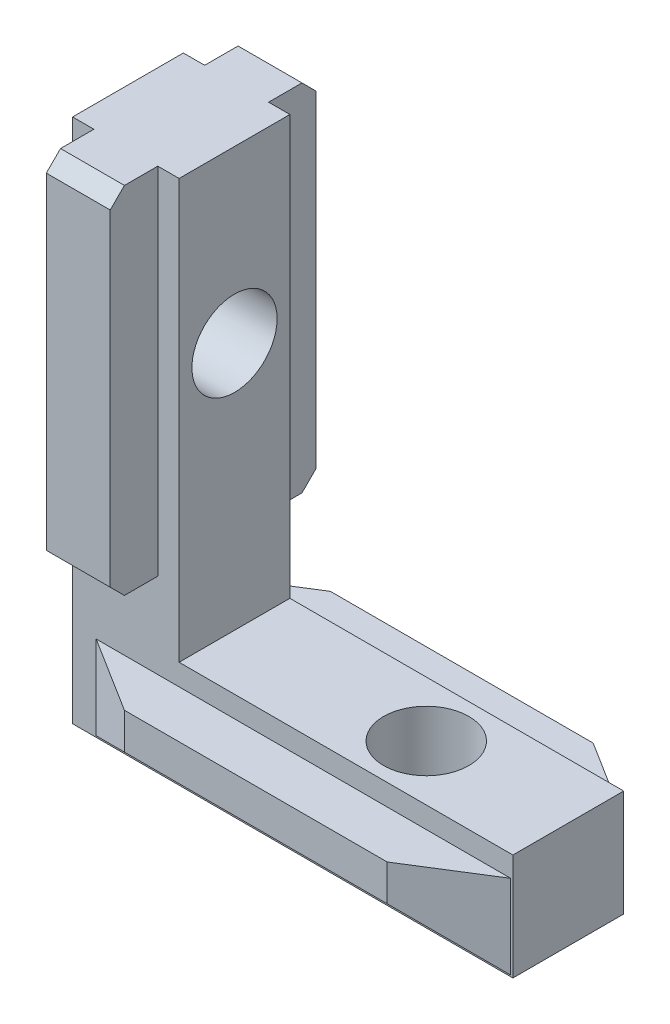
SolidWorks part; units mm, degrees
ref_plane "前视基准面" through (0, 0, 0) normal (0, 0, 1) x (1, 0, 0)
ref_plane "上视基准面" through (0, 0, 0) normal (0, 1, 0) x (1, 0, 0)
ref_plane "右视基准面" through (0, 0, 0) normal (1, 0, 0) x (0, 0, -1)
other "Configuration Table"
ref_plane "基准面1" through (0, 0, 3.9) normal (0, 0, 1) x (1, 0, 0)
sketch "草图1" plane through (0, 0, 3.9) normal (0, 0, 1) x (1, 0, 0)
  line L0 (31, 37) -> (0, 37)
  line L1 (0, 37) -> (0, 0)
  line L2 (0, 0) -> (31, 0)
  line L3 (31, 0) -> (31, 37)
extrude "凸台-拉伸1" add sketch "草图1" against normal blind 7.8
sketch "草图2" plane through (0, 0, -3.9) normal (0, 0, -1) x (-1, 0, 0)
  line L0 (-31, 7.5) -> (-7.5, 7.5)
  line L1 (-7.5, 7.5) -> (-7.5, 37)
  line L2 (-7.5, 37) -> (-31, 37)
  line L3 (-31, 37) -> (-31, 7.5)
extrude "切除-拉伸1" cut sketch "草图2" against normal through all
sketch "草图3" plane through (0, 0, 3.9) normal (0, 0, 1) x (1, 0, 0)
  line L0 (1.6594, 6) -> (30.8406, 6)
  line L1 (30.8406, 6) -> (30.8406, 0.1)
  line L2 (30.8406, 0.1) -> (1.6594, 0.1)
  line L3 (1.6594, 0.1) -> (1.6594, 6)
extrude "凸台-拉伸2" add sketch "草图3" along normal blind 3.35
sketch "草图4" plane through (0, 0, 3.9) normal (0, 0, 1) x (1, 0, 0)
  line L0 (1.5, 12) -> (1.5, 37)
  line L1 (1.5, 37) -> (6, 37)
  line L2 (6, 37) -> (6, 12)
  line L3 (6, 12) -> (1.5, 12)
extrude "凸台-拉伸3" add sketch "草图4" along normal blind 3.35
sketch "草图5" plane through (0, 0, -3.9) normal (0, 0, -1) x (-1, 0, 0)
  line L0 (-6, 12) -> (-6, 37)
  line L1 (-6, 37) -> (-1.5, 37)
  line L2 (-1.5, 37) -> (-1.5, 12)
  line L3 (-1.5, 12) -> (-6, 12)
extrude "凸台-拉伸4" add sketch "草图5" along normal blind 3.35
sketch "草图6" plane through (0, 0, -3.9) normal (0, 0, -1) x (-1, 0, 0)
  line L0 (-1.6594, 6) -> (-1.6594, 0.1)
  line L1 (-1.6594, 0.1) -> (-30.8406, 0.1)
  line L2 (-30.8406, 0.1) -> (-30.8406, 6)
  line L3 (-30.8406, 6) -> (-1.6594, 6)
extrude "凸台-拉伸5" add sketch "草图6" along normal blind 3.35
draft "拔模1" type of draft neutral plane draft angle 45 faces to draft 1 face at (16.25, 0.1, -5.575) neutral plane through (0, 0, -3.9) neutral plane normal (0, 0, -1) parameters "D1"=45
draft "拔模2" type of draft neutral plane draft angle 45 faces to draft 1 face at (16.25, 0.1, 5.575) neutral plane through (0, 0, 3.9) neutral plane normal (0, 0, 1) parameters "D1"=45
draft "拔模3" type of draft neutral plane draft angle 57.901 faces to draft 2 face at (30.8406, 3.8875, -5.575) face at (1.6594, 3.8875, -5.575) neutral plane through (0, 0, -3.9) neutral plane normal (0, 0, -1) parameters "D1"=57.901
draft "拔模4" type of draft neutral plane draft angle 57.901 faces to draft 2 face at (30.8406, 3.8875, 5.575) face at (1.6594, 3.8875, 5.575) neutral plane through (0, 0, 3.9) neutral plane normal (0, 0, 1) parameters "D1"=57.901
hole_wizard "Ø6.0 (6) 直径孔1" positions "草图8" profile "草图7" hole size "Ø6.0" standard "ANSI Metric"
sketch "草图8" plane through (7.5, 0, 0) normal (1, 0, 0) x (0, 0, -1)
  point P0 (0, 25)
sketch "草图7" plane through (7.5, 25, 0) normal (0, 1, 0) x (0, 0, -1)
  line L0 (0, 0) -> (0, 7.5)
  line L1 (0, 7.5) -> (3, 7.5)
  line L2 (3, 7.5) -> (3, 0)
  line L5 (3, 0) -> (0, 0)
  line L11 (0, -6.35) -> (0, 107.95) construction
  dimension "通孔孔直径" = 6
  dimension "通孔孔深度" = 7.5
hole_wizard "Ø6.0 (6) 直径孔2" positions "草图10" profile "草图9" hole size "Ø6.0" standard "ANSI Metric"
sketch "草图10" plane through (0, 0, 0) normal (0, -1, 0) x (-1, 0, 0)
  point P0 (-21, 0)
sketch "草图9" plane through (21, 0, 0) normal (1, 0, 0) x (0, 0, -1)
  line L0 (0, 0) -> (0, 37)
  line L1 (0, 37) -> (3, 37)
  line L2 (3, 37) -> (3, 0)
  line L5 (3, 0) -> (0, 0)
  line L11 (0, -6.35) -> (0, 107.95) construction
  dimension "通孔孔直径" = 6
  dimension "通孔孔深度" = 37
chamfer "倒角1" distance 1 angle 45 4 edges at (3.75, 37, -7.25) (3.75, 37, 7.25) (3.75, 12, 7.25) (3.75, 12, -7.25)
